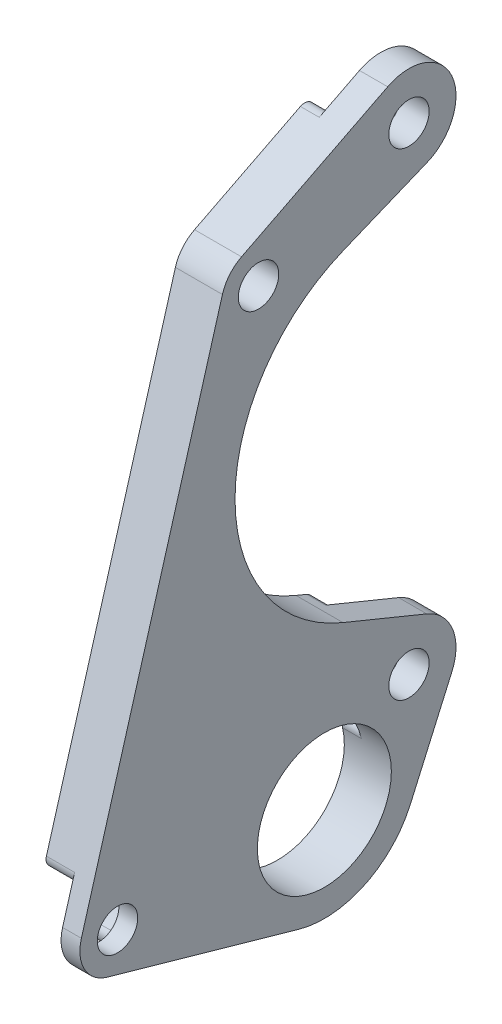
SolidWorks part; units mm, degrees
material "ABS"
ref_plane "前视基准面" through (0, 0, 0) normal (0, 0, 1) x (1, 0, 0)
ref_plane "上视基准面" through (0, 0, 0) normal (0, 1, 0) x (1, 0, 0)
ref_plane "右视基准面" through (0, 0, 0) normal (1, 0, 0) x (0, 0, -1)
other "Configuration Table"
sketch "草图1" plane through (0, 0, 0) normal (1, 0, 0) x (0, 0, -1)
  line L0 (-23.0909, -3.8484) -> (-2.7273, -9.6209)
  line L1 (9.1473, -4.0407) -> (13.5736, 5.9797)
  line L2 (10.8974, 12.626) -> (1.9795, 16.2839)
  line L3 (1.9795, 50.5161) -> (10.8974, 54.174)
  line L4 (6.7369, 63.2585) -> (-8.8105, 55.3668)
  line L5 (-10.8422, 52.9126) -> (-25.8422, 1.1126)
  circle A0 centre (9, 58.8) radius 2.15
  circle A1 centre (0, 0) radius 7.075 construction
  circle A2 centre (-22, 0) radius 2.15
  circle A3 centre (-7, 51.8) radius 2.15
  circle A4 centre (9, 8) radius 2.15
  arc A5 (-2.7273, -9.6209) -> (9.1473, -4.0407) centre (0, 0) ccw
  arc A6 (13.5736, 5.9797) -> (10.8974, 12.626) centre (9, 8) ccw
  arc A7 (1.9795, 50.5161) -> (1.9795, 16.2839) centre (9, 33.4) ccw
  arc A8 (10.8974, 54.174) -> (6.7369, 63.2585) centre (9, 58.8) ccw
  arc A9 (-8.8105, 55.3668) -> (-10.8422, 52.9126) centre (-7, 51.8) ccw
  arc A10 (-25.8422, 1.1126) -> (-23.0909, -3.8484) centre (-22, 0) ccw
  circle A11 centre (0, 0) radius 7.125
  dimension "D1" = 14.15
  dimension "D2" = 14.25
extrude "凸台-拉伸1" add sketch "草图1" along normal blind 5
sketch "草图2" plane through (0, 0, 0) normal (-1, 0, 0) x (0, 0, 1)
  circle A0 centre (22, 0) radius 4.5
  dimension "D1" = 9
extrude "切除-拉伸1" cut sketch "草图2" against normal blind 3
fillet "圆角1" radius 1 2 edges at (1.5, -4.4106, 21.1075) (1.5, 3.0928, 25.2687)
sketch "草图3" plane through (0, 0, 0) normal (-1, 0, 0) x (0, 0, 1)
  line L0 (-3.75, 58.8) -> (-3.75, 51.2424)
  line L1 (-1.9795, 50.5161) -> (-10.8974, 54.174) construction
  line L2 (-3.75, 51.2424) -> (-9.4164, 53.5665)
  line L3 (-3.75, 8) -> (-3.75, 15.5576)
  line L4 (-10.8974, 12.626) -> (-1.9795, 16.2839) construction
  line L5 (-9.4164, 13.2335) -> (-3.75, 15.5576)
  arc A0 (-3.75, 58.8) -> (-9.4164, 53.5665) centre (-9, 58.8) ccw
  arc A1 (-9.4164, 13.2335) -> (-3.75, 8) centre (-9, 8) ccw
  dimension "D1" = 10.5
extrude "切除-拉伸2" cut sketch "草图3" against normal blind 2
fillet "圆角2" radius 1 6 edges at (1, 3.5868, -6.1563) (1, 5.6933, -4.2839) (1, 15.5576, -3.75) (1, 62.534, -5.3095) (1, 4.5154, -12.9268) (1, 51.2424, -3.75)
